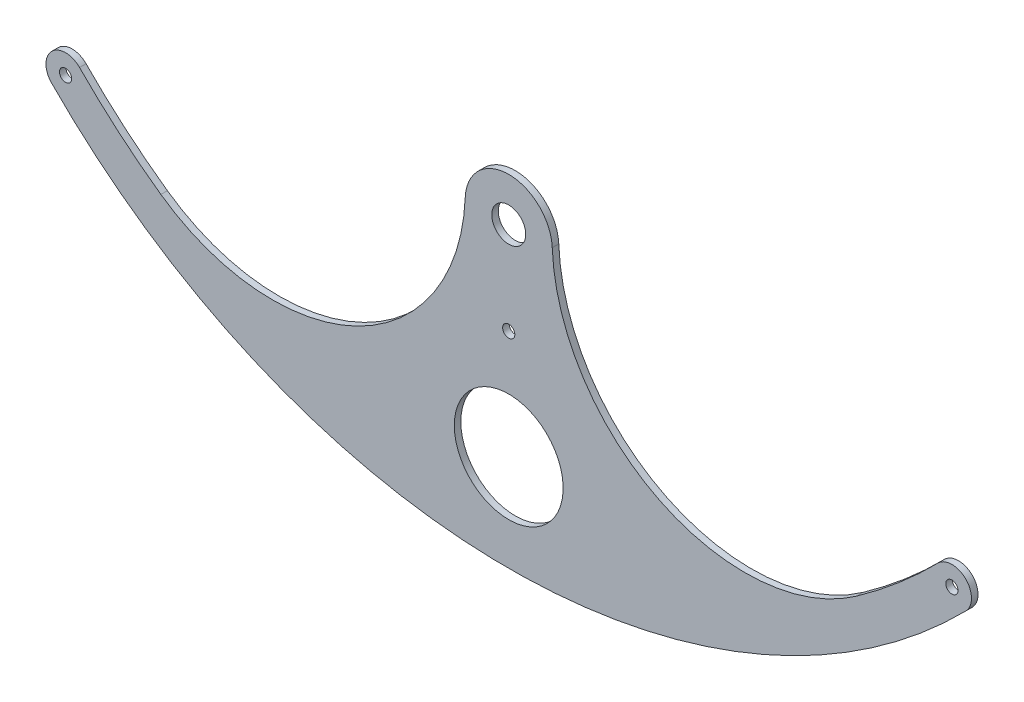
SolidWorks part; units mm, degrees
ref_plane "Front Plane" through (0, 0, 0) normal (0, 0, 1) x (1, 0, 0)
ref_plane "Top Plane" through (0, 0, 0) normal (0, 1, 0) x (1, 0, 0)
ref_plane "Right Plane" through (0, 0, 0) normal (1, 0, 0) x (0, 0, -1)
sketch "Sketch1" plane through (0, 0, 0) normal (0, 0, 1) x (1, 0, 0)
  line L0 (0, 0) -> (0, 37.2375) construction
  line L1 (0, 0) -> (0, -39.0149) construction
  circle A0 centre (0, 0) radius 1.778
  circle A1 centre (129.286, 0) radius 1.778
  circle A2 centre (-129.286, 0) radius 1.778
  arc A3 (-135.001, 0) -> (-133.363, -4.0049) centre (-129.286, 0) ccw
  arc A4 (133.363, -4.0049) -> (135.001, 0) centre (129.286, 0) ccw
  arc A5 (-133.363, -4.0049) -> (133.363, -4.0049) centre (0, 127) ccw
  arc A6 (-125.209, 4.0049) -> (-133.363, -4.0049) centre (-129.286, 0) ccw
  arc A7 (133.363, -4.0049) -> (125.209, 4.0049) centre (129.286, 0) ccw
  arc A8 (-125.209, 4.0049) -> (-101.4783, -16.2035) centre (0, 127) ccw
  circle A9 centre (0, 26.924) radius 4.953
  arc A10 (12.6895, 27.4394) -> (-12.6895, 27.4394) centre (0, 26.924) ccw
  arc A11 (-101.4783, -16.2035) -> (-12.6895, 27.4394) centre (-68.9328, 29.7238) ccw
  arc A12 (101.4783, -16.2035) -> (12.6895, 27.4394) centre (68.9328, 29.7238) cw
  arc A13 (101.4783, -16.2035) -> (125.209, 4.0049) centre (0, 127) ccw
  circle A14 centre (0, 127) radius 175.5138 construction
  circle A15 centre (0, 127) radius 186.9438 construction
  circle A16 centre (0, -31.75) radius 15.875
  point P18 (178.7752, 181.6571)
  point P25 (167.8447, 178.3153)
  dimension "D1" = 3.556
  dimension "D2" = 3.556
  dimension "D3" = 3.556
  dimension "D6" = 11.43
  dimension "D7" = 11.43
  dimension "D10" = 9.906
  dimension "D12" = 25.4
  dimension "D14" = 31.75
  dimension "D4" = 129.286
  dimension "D5" = 129.286
  dimension "D8" = 127
  dimension "D11" = 26.924
  dimension "D13" = 0
  dimension "D15" = 31.75
  dimension "D9" = 11.43
extrude "Boss-Extrude1" add sketch "Sketch1" along normal blind 1.905
